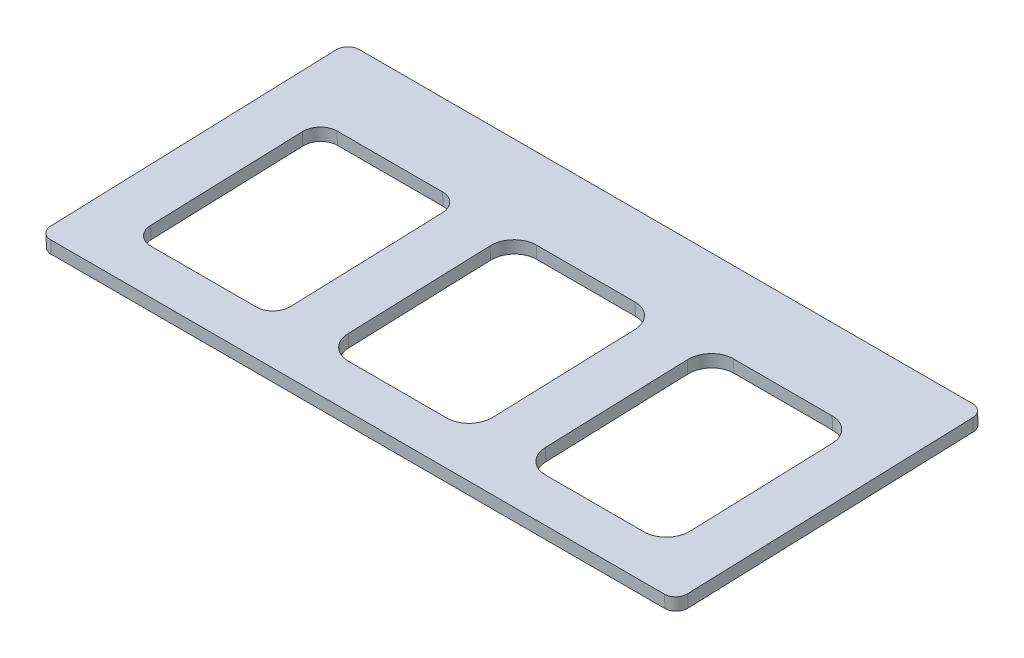
SolidWorks part; units mm, degrees
ref_plane "Front Plane" through (0, 0, 0) normal (0, 0, 1) x (1, 0, 0)
ref_plane "Top Plane" through (0, 0, 0) normal (0, 1, 0) x (1, 0, 0)
ref_plane "Right Plane" through (0, 0, 0) normal (1, 0, 0) x (0, 0, -1)
sketch "Sketch1" plane through (0, -71.9872, -2.5138) normal (0, -0.9994, -0.0349) x (1, 0, 0)
  line L0 (-22.025, -32.5624) -> (-22.025, -6.2624) construction
  line L1 (-25.025, -3.2624) -> (-43.325, -3.2624) construction
  line L2 (-46.325, -6.2624) -> (-46.325, -32.5624) construction
  line L3 (-43.325, -35.5624) -> (-25.025, -35.5624) construction
  line L4 (-53.175, -49.2404) -> (53.175, -49.2404)
  line L5 (55.175, -47.2404) -> (55.175, 2.2116)
  line L6 (53.175, 4.2116) -> (-53.175, 4.2116)
  line L7 (-55.175, 2.2116) -> (-55.175, -47.2404)
  line L8 (-53.175, -49.2404) -> (53.175, -49.2404)
  line L9 (55.175, -47.2404) -> (55.175, 2.2116)
  line L10 (53.175, 4.2116) -> (-53.175, 4.2116)
  line L11 (-55.175, 2.2116) -> (-55.175, -47.2404)
  line L12 (-22.025, -32.5624) -> (-22.025, -6.2624)
  line L13 (-25.025, -3.2624) -> (-43.325, -3.2624)
  line L14 (-46.325, -6.2624) -> (-46.325, -32.5624)
  line L15 (-43.325, -35.5624) -> (-25.025, -35.5624)
  line L16 (12.15, -19.4124) -> (21.225, -19.4124) construction
  line L17 (-8.95, -3.1124) -> (8.15, -3.1124)
  line L18 (-12.95, -7.1124) -> (-12.95, -31.7124)
  line L19 (-8.95, -35.7124) -> (8.15, -35.7124)
  line L20 (12.15, -7.1124) -> (12.15, -31.7124)
  line L21 (25.225, -3.1124) -> (42.325, -3.1124)
  line L22 (21.225, -7.1124) -> (21.225, -31.7124)
  line L23 (25.225, -35.7124) -> (42.325, -35.7124)
  line L24 (46.325, -7.1124) -> (46.325, -31.7124)
  line L25 (-12.95, -19.4124) -> (-22.025, -19.4124) construction
  line L26 (-46.325, -19.4124) -> (-51.3954, -19.4124) construction
  line L27 (-52.1716, 2.8156) -> (-50.754, -37.78) construction
  line L28 (46.325, -19.4124) -> (51.3954, -19.4124) construction
  line L29 (50.754, -37.78) -> (52.1716, 2.8156) construction
  arc A0 (-22.025, -6.2624) -> (-25.025, -3.2624) centre (-25.025, -6.2624) ccw construction
  arc A1 (-43.325, -3.2624) -> (-46.325, -6.2624) centre (-43.325, -6.2624) ccw construction
  arc A2 (-46.325, -32.5624) -> (-43.325, -35.5624) centre (-43.325, -32.5624) ccw construction
  arc A3 (-25.025, -35.5624) -> (-22.025, -32.5624) centre (-25.025, -32.5624) ccw construction
  arc A4 (53.175, -49.2404) -> (55.175, -47.2404) centre (53.175, -47.2404) ccw
  arc A5 (55.175, 2.2116) -> (53.175, 4.2116) centre (53.175, 2.2116) ccw
  arc A6 (-53.175, 4.2116) -> (-55.175, 2.2116) centre (-53.175, 2.2116) ccw
  arc A7 (-55.175, -47.2404) -> (-53.175, -49.2404) centre (-53.175, -47.2404) ccw
  arc A8 (53.175, -49.2404) -> (55.175, -47.2404) centre (53.175, -47.2404) ccw
  arc A9 (55.175, 2.2116) -> (53.175, 4.2116) centre (53.175, 2.2116) ccw
  arc A10 (-53.175, 4.2116) -> (-55.175, 2.2116) centre (-53.175, 2.2116) ccw
  arc A11 (-55.175, -47.2404) -> (-53.175, -49.2404) centre (-53.175, -47.2404) ccw
  arc A12 (-22.025, -6.2624) -> (-25.025, -3.2624) centre (-25.025, -6.2624) ccw
  arc A13 (-43.325, -3.2624) -> (-46.325, -6.2624) centre (-43.325, -6.2624) ccw
  arc A14 (-46.325, -32.5624) -> (-43.325, -35.5624) centre (-43.325, -32.5624) ccw
  arc A15 (-25.025, -35.5624) -> (-22.025, -32.5624) centre (-25.025, -32.5624) ccw
  arc A16 (42.325, -35.7124) -> (46.325, -31.7124) centre (42.325, -31.7124) ccw
  arc A17 (42.325, -3.1124) -> (46.325, -7.1124) centre (42.325, -7.1124) cw
  arc A18 (21.225, -31.7124) -> (25.225, -35.7124) centre (25.225, -31.7124) ccw
  arc A19 (25.225, -3.1124) -> (21.225, -7.1124) centre (25.225, -7.1124) ccw
  arc A20 (-12.95, -31.7124) -> (-8.95, -35.7124) centre (-8.95, -31.7124) ccw
  arc A21 (8.15, -35.7124) -> (12.15, -31.7124) centre (8.15, -31.7124) ccw
  arc A22 (8.15, -3.1124) -> (12.15, -7.1124) centre (8.15, -7.1124) cw
  arc A23 (-8.95, -3.1124) -> (-12.95, -7.1124) centre (-8.95, -7.1124) ccw
  point P54 (-12.95, -35.7124)
  point P57 (12.15, -35.7124)
  point P62 (-12.95, -3.1124)
  dimension "D4" = 4
  dimension "D2" = 25.1
  dimension "D3" = 32.6
  dimension "D1" = 0
extrude "Boss-Extrude1" add sketch "Sketch1" against normal up to surface (2.2 mm away)
